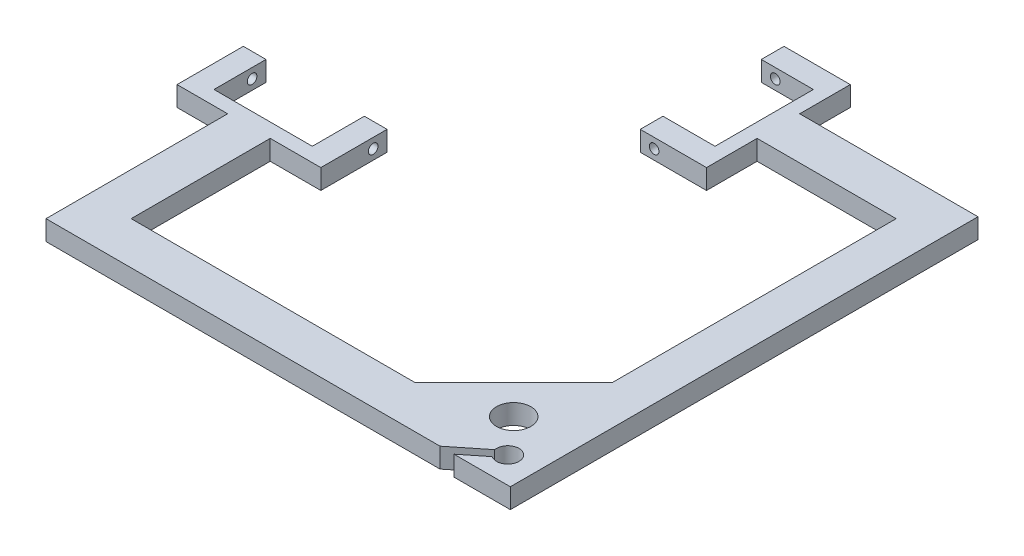
SolidWorks part; units mm, degrees
ref_plane "Front Plane" through (0, 0, 0) normal (0, 0, 1) x (1, 0, 0)
ref_plane "Top Plane" through (0, 0, 0) normal (0, 1, 0) x (1, 0, 0)
ref_plane "Right Plane" through (0, 0, 0) normal (1, 0, 0) x (0, 0, -1)
sketch "Sketch1" plane through (0, 0, 0) normal (0, 1, 0) x (1, 0, 0)
  line L0 (-87.25, -27.0052) -> (-87.25, -45.3452)
  line L1 (-87.25, -45.3452) -> (-52.6, -45.3452)
  line L2 (-52.6, -45.3452) -> (-52.6, -27.0052)
  line L3 (-52.6, -27.0052) -> (-44.6, -27.0052)
  line L4 (-44.6, -27.0052) -> (-44.6, -50.3452)
  line L5 (-44.6, -50.3452) -> (-62.425, -50.3452)
  line L6 (-87.25, -27.0052) -> (-95.25, -27.0052)
  line L7 (-95.25, -27.0052) -> (-95.25, -50.3452)
  line L8 (-95.25, -50.3452) -> (-77.425, -50.3452)
  line L9 (-77.425, -50.3452) -> (-77.425, -114.3452)
  line L10 (-62.425, -50.3452) -> (-62.425, -99.3452)
  line L11 (-77.425, -114.3452) -> (37.575, -114.3452)
  line L12 (-62.425, -99.3452) -> (37.575, -99.3452)
  line L14 (23.34, 35.4198) -> (23.34, 17.5948)
  line L15 (23.34, 17.5948) -> (0, 17.5948)
  line L16 (0, 17.5948) -> (0, 25.5948)
  line L17 (0, 25.5948) -> (18.34, 25.5948)
  line L18 (18.34, 25.5948) -> (18.34, 60.2448)
  line L19 (18.34, 60.2448) -> (0, 60.2448)
  line L20 (0, 60.2448) -> (0, 68.2448)
  line L21 (0, 68.2448) -> (23.34, 68.2448)
  line L22 (23.34, 68.2448) -> (23.34, 50.4198)
  line L28 (23.34, 35.4198) -> (72.34, 35.4198)
  line L29 (72.34, 35.4198) -> (72.34, -64.5802)
  line L30 (23.34, 50.4198) -> (86.165, 50.4198)
  line L31 (86.165, 50.4198) -> (86.165, -65.7552)
  line L32 (72.34, -64.5802) -> (37.575, -99.3452)
  line L34 (86.165, -114.3452) -> (86.165, -65.7552)
  line L35 (72.0905, -105.784) -> (61.3976, -114.3452)
  line L36 (66.3, -114.3452) -> (73.7711, -108.3635)
  line L37 (66.3, -114.3452) -> (86.165, -114.3452)
  line L38 (61.3976, -114.3452) -> (37.575, -114.3452)
  circle A2 centre (65.34, -92.3452) radius 6.05
  arc A3 (73.7711, -108.3635) -> (72.0905, -105.784) centre (75.995, -105.0775) ccw
  dimension "D11" = 7
  dimension "D12" = 7
  dimension "D13" = 12.1
  dimension "D1" = 8
  dimension "D2" = 18.34
  dimension "D3" = 5
  dimension "D4" = 34.65
  dimension "D5" = 100
  dimension "D6" = 15
  dimension "D7" = 49
  dimension "D8" = 15
  dimension "D9" = 70.94
  dimension "D10" = 70.94
  dimension "D14" = 4.9023
extrude "Boss-Extrude1" add sketch "Sketch1" along normal blind 7
sketch "Sketch2" plane through (0, 0, -17.5948) normal (0, 0, 1) x (1, 0, 0)
  line L0 (0, 7) -> (0, 0) construction
  line L1 (0, 7) -> (23.34, 7) construction
  line L3 (0, 0) -> (23.34, 0) construction
  circle A0 centre (4.9, 3.5) radius 1.7
  dimension "D1" = 3.4
  dimension "D2" = 4.9
  dimension "D3" = 3.5
  dimension "D4" = 3.5
extrude "Cut-Extrude1" cut sketch "Sketch2" against normal blind 60
sketch "Sketch3" plane through (-44.6, 0, 0) normal (1, 0, 0) x (0, 0, -1)
  line L0 (-27.0052, 7) -> (-27.0052, 0) construction
  line L1 (-50.3452, 7) -> (-27.0052, 7) construction
  line L2 (-50.3452, 0) -> (-27.0052, 0) construction
  circle A0 centre (-31.9052, 3.5) radius 1.7
  dimension "D1" = 3.4
  dimension "D3" = 3.5
  dimension "D4" = 3.5
  dimension "D2" = 4.9
extrude "Cut-Extrude2" cut sketch "Sketch3" against normal blind 60
